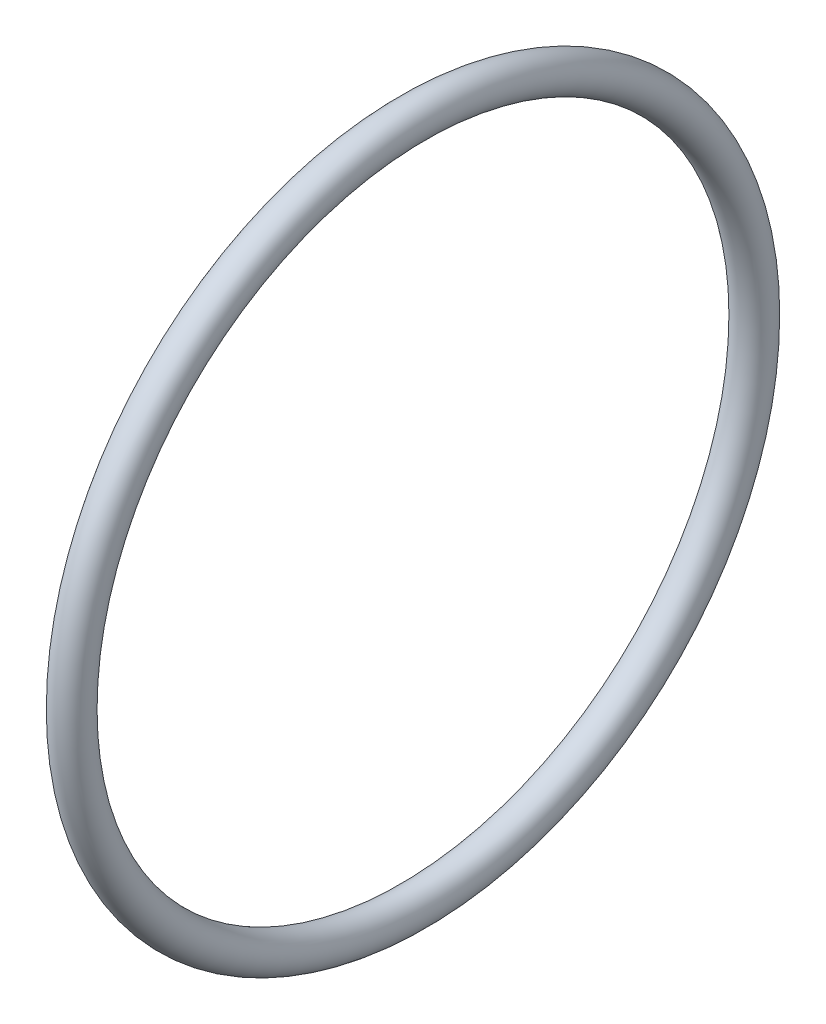
SolidWorks part; units mm, degrees
ref_plane "Front Plane" through (0, 0, 0) normal (0, 0, 1) x (1, 0, 0)
ref_plane "Top Plane" through (0, 0, 0) normal (0, 1, 0) x (1, 0, 0)
ref_plane "Right Plane" through (0, 0, 0) normal (1, 0, 0) x (0, 0, -1)
sketch "Sketch1" plane through (0, 0, 0) normal (0, 0, 1) x (1, 0, 0)
  line L0 (0, -2.5) -> (0, -47.5) construction
  line L1 (-2.6651, -47.5) -> (3.5672, -47.5) construction
  circle A0 centre (0, 0) radius 2.5
  dimension "D1" = 5
  dimension "D2" = 45
revolve "Revolve1" add sketch "Sketch1" angle 360 about L1
sketch "Sketch6" plane through (0, 0, 0) normal (0, 1, 0) x (1, 0, 0)
  line L0 (-2.5, 47.5) -> (-2.5, -47.5) construction
  line L1 (2.5, -47.5) -> (2.5, 47.5) construction
  line L2 (-2.5, 47.5) -> (-2.5, -47.5) construction
  line L3 (2.5, -47.5) -> (2.5, 47.5) construction
sketch "Sketch8" plane through (0, 0, 0) normal (1, 0, 0) x (0, 0, -1)
  circle A0 centre (0, -47.5) radius 50 construction
  circle A1 centre (0, -47.5) radius 45 construction
  circle A2 centre (0, -47.5) radius 50 construction
  circle A3 centre (0, -47.5) radius 45 construction
